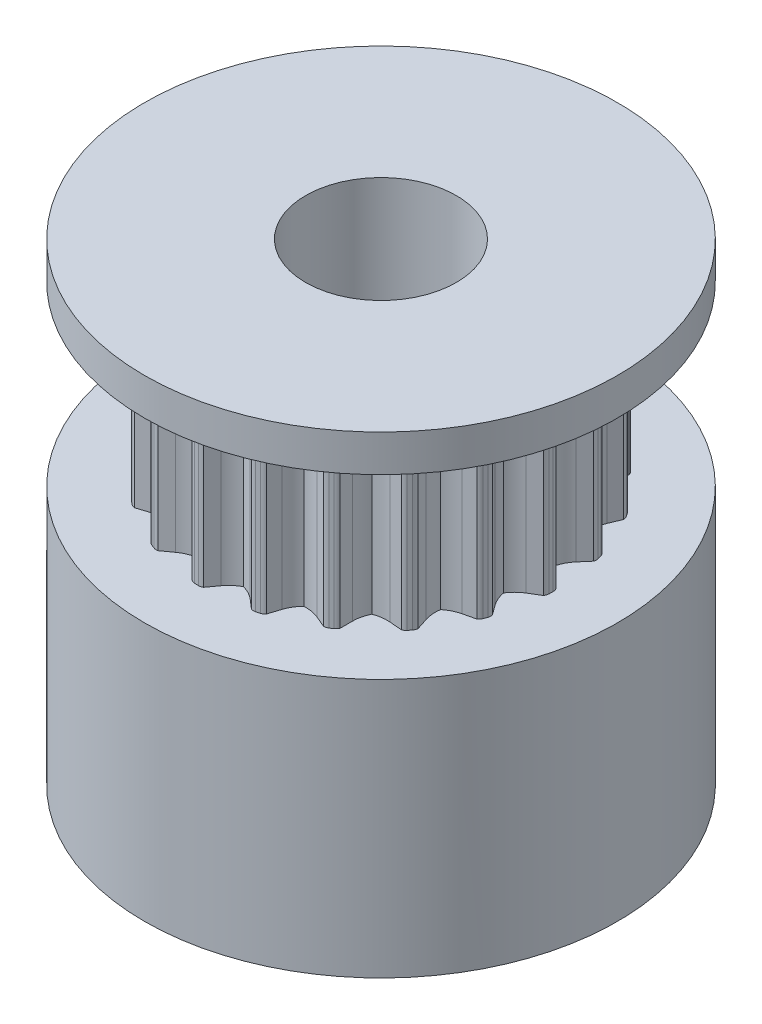
SolidWorks part; units mm, degrees
ref_plane "前视基准面" through (0, 0, 0) normal (0, 0, 1) x (1, 0, 0)
ref_plane "上视基准面" through (0, 0, 0) normal (0, 1, 0) x (1, 0, 0)
ref_plane "右视基准面" through (0, 0, 0) normal (1, 0, 0) x (0, 0, -1)
other "Configuration Table"
sketch "草图1" plane through (0, 0, 0) normal (0, 1, 0) x (1, 0, 0)
  line L2 (-3.3768, 4.9596) -> (-3.2674, 5.0323)
  line L3 (-3.4667, 4.8471) -> (-3.4667, 4.4267)
  line L4 (-3.1289, 5.0717) -> (-2.7413, 4.9091)
  line L5 (-1.6789, 5.7603) -> (-1.5524, 5.7957)
  line L6 (-1.7992, 5.6811) -> (-1.9291, 5.2813)
  line L7 (-1.4085, 5.7904) -> (-1.0901, 5.5159)
  line L8 (0.1833, 5.9972) -> (0.3145, 5.9918)
  line L9 (0.0445, 5.9591) -> (-0.2026, 5.619)
  line L10 (0.4497, 5.9422) -> (0.6678, 5.5828)
  line L11 (2.0276, 5.647) -> (2.1507, 5.6013)
  line L12 (1.8837, 5.6537) -> (1.5436, 5.4066)
  line L13 (2.264, 5.5124) -> (2.3603, 5.1032)
  line L14 (3.6734, 4.7441) -> (3.7763, 4.6626)
  line L15 (3.5386, 4.7949) -> (3.1388, 4.665)
  line L16 (3.8566, 4.543) -> (3.8218, 4.1241)
  line L17 (4.9596, 3.3768) -> (5.0323, 3.2674)
  line L18 (4.8471, 3.4667) -> (4.4267, 3.4667)
  line L19 (5.0717, 3.1289) -> (4.9091, 2.7413)
  line L20 (5.7603, 1.6789) -> (5.7957, 1.5524)
  line L21 (5.6811, 1.7992) -> (5.2813, 1.9291)
  line L22 (5.7904, 1.4085) -> (5.5159, 1.0901)
  line L23 (5.9972, -0.1833) -> (5.9918, -0.3145)
  line L24 (5.9591, -0.0445) -> (5.619, 0.2026)
  line L25 (5.9422, -0.4497) -> (5.5828, -0.6678)
  line L26 (5.647, -2.0276) -> (5.6013, -2.1507)
  line L27 (5.6537, -1.8837) -> (5.4066, -1.5436)
  line L28 (5.5124, -2.264) -> (5.1032, -2.3603)
  line L29 (4.7441, -3.6734) -> (4.6626, -3.7763)
  line L30 (4.7949, -3.5386) -> (4.665, -3.1388)
  line L31 (4.543, -3.8566) -> (4.1241, -3.8218)
  line L32 (3.3768, -4.9596) -> (3.2674, -5.0323)
  line L33 (3.4667, -4.8471) -> (3.4667, -4.4267)
  line L34 (3.1289, -5.0717) -> (2.7413, -4.9091)
  line L35 (1.6789, -5.7603) -> (1.5524, -5.7957)
  line L36 (1.7992, -5.6811) -> (1.9291, -5.2813)
  line L37 (1.4085, -5.7904) -> (1.0901, -5.5159)
  line L38 (-0.1833, -5.9972) -> (-0.3145, -5.9918)
  line L39 (-0.0445, -5.9591) -> (0.2026, -5.619)
  line L40 (-0.4497, -5.9422) -> (-0.6678, -5.5828)
  line L41 (-2.0276, -5.647) -> (-2.1507, -5.6013)
  line L42 (-1.8837, -5.6537) -> (-1.5436, -5.4066)
  line L43 (-2.264, -5.5124) -> (-2.3603, -5.1032)
  line L44 (-3.6734, -4.7441) -> (-3.7763, -4.6626)
  line L45 (-3.5386, -4.7949) -> (-3.1388, -4.665)
  line L46 (-3.8566, -4.543) -> (-3.8218, -4.1241)
  line L47 (-4.9596, -3.3768) -> (-5.0323, -3.2674)
  line L48 (-4.8471, -3.4667) -> (-4.4267, -3.4667)
  line L49 (-5.0717, -3.1289) -> (-4.9091, -2.7413)
  line L50 (-5.7603, -1.6789) -> (-5.7957, -1.5524)
  line L51 (-5.6811, -1.7992) -> (-5.2813, -1.9291)
  line L52 (-5.7904, -1.4085) -> (-5.5159, -1.0901)
  line L53 (-5.9972, 0.1833) -> (-5.9918, 0.3145)
  line L54 (-5.9591, 0.0445) -> (-5.619, -0.2026)
  line L55 (-5.9422, 0.4497) -> (-5.5828, 0.6678)
  line L56 (-5.647, 2.0276) -> (-5.6013, 2.1507)
  line L57 (-5.6537, 1.8837) -> (-5.4066, 1.5436)
  line L58 (-5.5124, 2.264) -> (-5.1032, 2.3603)
  line L59 (-4.7441, 3.6734) -> (-4.6626, 3.7763)
  line L60 (-4.7949, 3.5386) -> (-4.665, 3.1388)
  line L61 (-4.543, 3.8566) -> (-4.1241, 3.8218)
  arc A1 (-3.4667, 4.4267) -> (-3.5892, 3.9002) centre (-4.6588, 4.4267) cw
  arc A2 (-3.3768, 4.9596) -> (-3.4667, 4.8471) centre (-3.2292, 4.7494) ccw
  arc A3 (-2.7413, 4.9091) -> (-2.2083, 4.8185) centre (-2.2801, 6.0085) ccw
  arc A4 (-3.2674, 5.0323) -> (-3.1289, 5.0717) centre (-3.1307, 4.8149) cw
  arc A5 (-1.9291, 5.2813) -> (-2.2083, 4.8185) centre (-3.0629, 5.6497) cw
  arc A6 (-1.6789, 5.7603) -> (-1.7992, 5.6811) centre (-1.6035, 5.5148) ccw
  arc A7 (-1.5524, 5.7957) -> (-1.4085, 5.7904) centre (-1.4896, 5.5467) cw
  arc A8 (-1.0901, 5.5159) -> (-0.6113, 5.2651) centre (-0.3118, 6.419) ccw
  arc A9 (-0.2026, 5.619) -> (-0.6113, 5.2651) centre (-1.1671, 6.3197) cw
  arc A10 (0.1833, 5.9972) -> (0.0445, 5.9591) centre (0.1792, 5.7404) ccw
  arc A11 (0.3145, 5.9918) -> (0.4497, 5.9422) centre (0.2974, 5.7355) cw
  arc A12 (0.6678, 5.5828) -> (1.0457, 5.1963) centre (1.687, 6.2012) ccw
  arc A13 (1.5436, 5.4066) -> (1.0457, 5.1963) centre (0.8429, 6.371) cw
  arc A14 (2.0276, 5.647) -> (1.8837, 5.6537) centre (1.9443, 5.4041) ccw
  arc A15 (2.1507, 5.6013) -> (2.264, 5.5124) centre (2.0552, 5.3629) cw
  arc A16 (2.3603, 5.1032) -> (2.6002, 4.6188) centre (3.5207, 5.3764) ccw
  arc A17 (3.1388, 4.665) -> (2.6002, 4.6188) centre (2.7704, 5.7987) cw
  arc A18 (3.6734, 4.7441) -> (3.5386, 4.7949) centre (3.5191, 4.5388) ccw
  arc A19 (3.7763, 4.6626) -> (3.8566, 4.543) centre (3.6118, 4.4653) cw
  arc A20 (3.8218, 4.1241) -> (3.9002, 3.5892) centre (5.0098, 4.0253) ccw
  arc A21 (4.4267, 3.4667) -> (3.9002, 3.5892) centre (4.4267, 4.6588) cw
  arc A22 (4.9596, 3.3768) -> (4.8471, 3.4667) centre (4.7494, 3.2292) ccw
  arc A23 (5.0323, 3.2674) -> (5.0717, 3.1289) centre (4.8149, 3.1307) cw
  arc A24 (4.9091, 2.7413) -> (4.8185, 2.2083) centre (6.0085, 2.2801) ccw
  arc A25 (5.2813, 1.9291) -> (4.8185, 2.2083) centre (5.6497, 3.0629) cw
  arc A26 (5.7603, 1.6789) -> (5.6811, 1.7992) centre (5.5148, 1.6035) ccw
  arc A27 (5.7957, 1.5524) -> (5.7904, 1.4085) centre (5.5467, 1.4896) cw
  arc A28 (5.5159, 1.0901) -> (5.2651, 0.6113) centre (6.419, 0.3118) ccw
  arc A29 (5.619, 0.2026) -> (5.2651, 0.6113) centre (6.3197, 1.1671) cw
  arc A30 (5.9972, -0.1833) -> (5.9591, -0.0445) centre (5.7404, -0.1792) ccw
  arc A31 (5.9918, -0.3145) -> (5.9422, -0.4497) centre (5.7355, -0.2974) cw
  arc A32 (5.5828, -0.6678) -> (5.1963, -1.0457) centre (6.2012, -1.687) ccw
  arc A33 (5.4066, -1.5436) -> (5.1963, -1.0457) centre (6.371, -0.8429) cw
  arc A34 (5.647, -2.0276) -> (5.6537, -1.8837) centre (5.4041, -1.9443) ccw
  arc A35 (5.6013, -2.1507) -> (5.5124, -2.264) centre (5.3629, -2.0552) cw
  arc A36 (5.1032, -2.3603) -> (4.6188, -2.6002) centre (5.3764, -3.5207) ccw
  arc A37 (4.665, -3.1388) -> (4.6188, -2.6002) centre (5.7987, -2.7704) cw
  arc A38 (4.7441, -3.6734) -> (4.7949, -3.5386) centre (4.5388, -3.5191) ccw
  arc A39 (4.6626, -3.7763) -> (4.543, -3.8566) centre (4.4653, -3.6118) cw
  arc A40 (4.1241, -3.8218) -> (3.5892, -3.9002) centre (4.0253, -5.0098) ccw
  arc A41 (3.4667, -4.4267) -> (3.5892, -3.9002) centre (4.6588, -4.4267) cw
  arc A42 (3.3768, -4.9596) -> (3.4667, -4.8471) centre (3.2292, -4.7494) ccw
  arc A43 (3.2674, -5.0323) -> (3.1289, -5.0717) centre (3.1307, -4.8149) cw
  arc A44 (2.7413, -4.9091) -> (2.2083, -4.8185) centre (2.2801, -6.0085) ccw
  arc A45 (1.9291, -5.2813) -> (2.2083, -4.8185) centre (3.0629, -5.6497) cw
  arc A46 (1.6789, -5.7603) -> (1.7992, -5.6811) centre (1.6035, -5.5148) ccw
  arc A47 (1.5524, -5.7957) -> (1.4085, -5.7904) centre (1.4896, -5.5467) cw
  arc A48 (1.0901, -5.5159) -> (0.6113, -5.2651) centre (0.3118, -6.419) ccw
  arc A49 (0.2026, -5.619) -> (0.6113, -5.2651) centre (1.1671, -6.3197) cw
  arc A50 (-0.1833, -5.9972) -> (-0.0445, -5.9591) centre (-0.1792, -5.7404) ccw
  arc A51 (-0.3145, -5.9918) -> (-0.4497, -5.9422) centre (-0.2974, -5.7355) cw
  arc A52 (-0.6678, -5.5828) -> (-1.0457, -5.1963) centre (-1.687, -6.2012) ccw
  arc A53 (-1.5436, -5.4066) -> (-1.0457, -5.1963) centre (-0.8429, -6.371) cw
  arc A54 (-2.0276, -5.647) -> (-1.8837, -5.6537) centre (-1.9443, -5.4041) ccw
  arc A55 (-2.1507, -5.6013) -> (-2.264, -5.5124) centre (-2.0552, -5.3629) cw
  arc A56 (-2.3603, -5.1032) -> (-2.6002, -4.6188) centre (-3.5207, -5.3764) ccw
  arc A57 (-3.1388, -4.665) -> (-2.6002, -4.6188) centre (-2.7704, -5.7987) cw
  arc A58 (-3.6734, -4.7441) -> (-3.5386, -4.7949) centre (-3.5191, -4.5388) ccw
  arc A59 (-3.7763, -4.6626) -> (-3.8566, -4.543) centre (-3.6118, -4.4653) cw
  arc A60 (-3.8218, -4.1241) -> (-3.9002, -3.5892) centre (-5.0098, -4.0253) ccw
  arc A61 (-4.4267, -3.4667) -> (-3.9002, -3.5892) centre (-4.4267, -4.6588) cw
  arc A62 (-4.9596, -3.3768) -> (-4.8471, -3.4667) centre (-4.7494, -3.2292) ccw
  arc A63 (-5.0323, -3.2674) -> (-5.0717, -3.1289) centre (-4.8149, -3.1307) cw
  arc A64 (-4.9091, -2.7413) -> (-4.8185, -2.2083) centre (-6.0085, -2.2801) ccw
  arc A65 (-5.2813, -1.9291) -> (-4.8185, -2.2083) centre (-5.6497, -3.0629) cw
  arc A66 (-5.7603, -1.6789) -> (-5.6811, -1.7992) centre (-5.5148, -1.6035) ccw
  arc A67 (-5.7957, -1.5524) -> (-5.7904, -1.4085) centre (-5.5467, -1.4896) cw
  arc A68 (-5.5159, -1.0901) -> (-5.2651, -0.6113) centre (-6.419, -0.3118) ccw
  arc A69 (-5.619, -0.2026) -> (-5.2651, -0.6113) centre (-6.3197, -1.1671) cw
  arc A70 (-5.9972, 0.1833) -> (-5.9591, 0.0445) centre (-5.7404, 0.1792) ccw
  arc A71 (-5.9918, 0.3145) -> (-5.9422, 0.4497) centre (-5.7355, 0.2974) cw
  arc A72 (-5.5828, 0.6678) -> (-5.1963, 1.0457) centre (-6.2012, 1.687) ccw
  arc A73 (-5.4066, 1.5436) -> (-5.1963, 1.0457) centre (-6.371, 0.8429) cw
  arc A74 (-5.647, 2.0276) -> (-5.6537, 1.8837) centre (-5.4041, 1.9443) ccw
  arc A75 (-5.6013, 2.1507) -> (-5.5124, 2.264) centre (-5.3629, 2.0552) cw
  arc A76 (-5.1032, 2.3603) -> (-4.6188, 2.6002) centre (-5.3764, 3.5207) ccw
  arc A77 (-4.665, 3.1388) -> (-4.6188, 2.6002) centre (-5.7987, 2.7704) cw
  arc A78 (-4.7441, 3.6734) -> (-4.7949, 3.5386) centre (-4.5388, 3.5191) ccw
  arc A79 (-4.6626, 3.7763) -> (-4.543, 3.8566) centre (-4.4653, 3.6118) cw
  arc A80 (-4.1241, 3.8218) -> (-3.5892, 3.9002) centre (-4.0253, 5.0098) ccw
  point P247 (0, 0)
  dimension "D1" = 20
extrude "凸台-拉伸1" add sketch "草图1" along normal mid plane 6
sketch "草图3" plane through (0, 3, 0) normal (0, 1, 0) x (1, 0, 0)
  circle A0 centre (0, 0) radius 8
  dimension "D1" = 16
extrude "凸台-拉伸2" add sketch "草图3" along normal blind 1.25
mirror "镜向1" about plane through (0, 0, 0) normal (0, 1, 0) of "凸台-拉伸2"
sketch "草图4" plane through (0, 4.25, 0) normal (0, 1, 0) x (1, 0, 0)
  circle A0 centre (0, 0) radius 2.55
  dimension "D1" = 5.1
extrude "切除-拉伸1" cut sketch "草图4" against normal through all
sketch "草图6" plane through (0, 0, 0) normal (0, 0, 1) x (1, 0, 0)
  line L0 (-8, -4.25) -> (-8, -11.75)
  line L1 (-8, -11.75) -> (0, -11.75)
  line L2 (0, -11.75) -> (0, -4.25) construction
  line L3 (-8, -4.25) -> (8, -4.25) construction
  line L4 (8, 4.25) -> (-8, 4.25) construction
  line L5 (-8, -4.25) -> (0, -4.25)
  line L6 (-2.5, -4.25) -> (-2.5, -11.75)
  dimension "D1" = 16
  dimension "D2" = 5
revolve "旋转1" add sketch "草图6" angle 360 about L2
